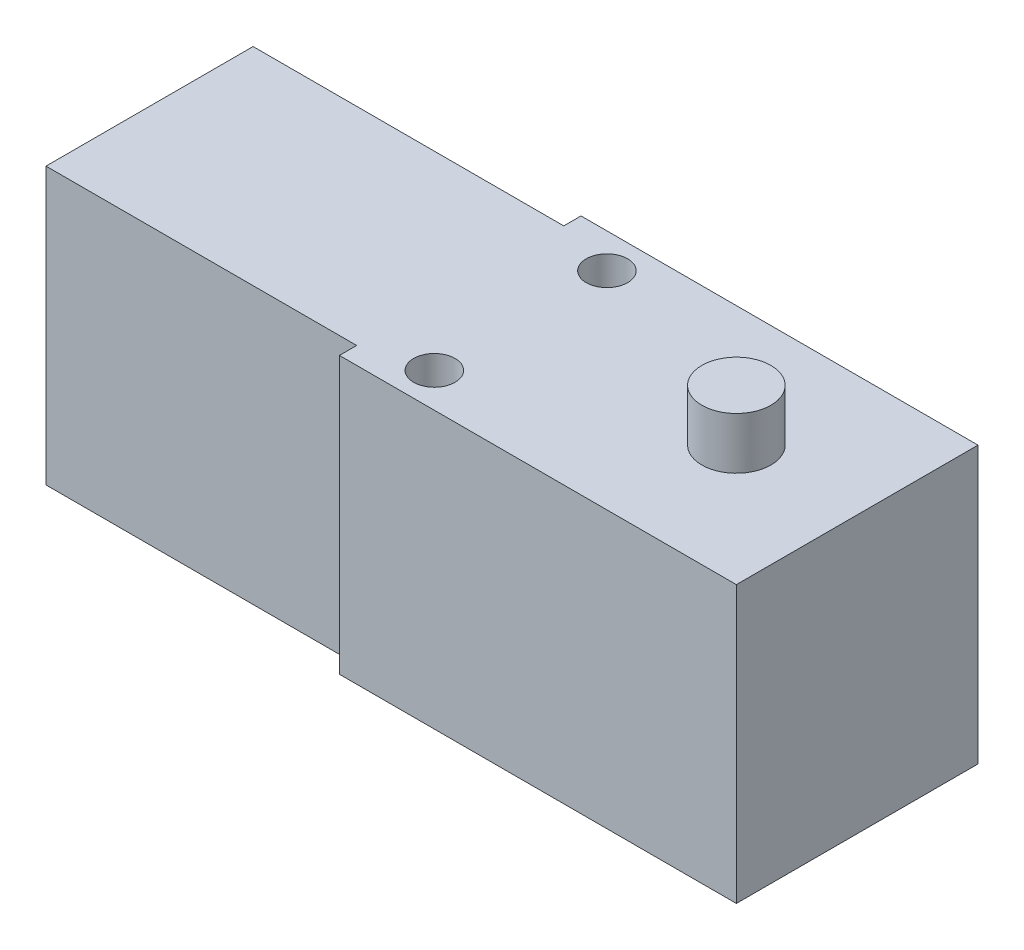
SolidWorks part; units mm, degrees
ref_plane "Front Plane" through (0, 0, 0) normal (0, 0, 1) x (1, 0, 0)
ref_plane "Top Plane" through (0, 0, 0) normal (0, 1, 0) x (1, 0, 0)
ref_plane "Right Plane" through (0, 0, 0) normal (1, 0, 0) x (0, 0, -1)
sketch "Sketch1" plane through (0, 0, 0) normal (0, 1, 0) x (1, 0, 0)
  line L0 (-28.575, 0) -> (36.5125, 0) construction
  line L1 (-28.575, -9.525) -> (0, -9.525)
  line L2 (-28.575, -9.525) -> (-28.575, 9.525)
  line L3 (-28.575, 9.525) -> (0, 9.525)
  line L4 (0, -9.525) -> (0, 9.525)
  line L5 (-28.575, -9.525) -> (0, 9.525) construction
  line L6 (-28.575, 9.525) -> (0, -9.525) construction
  line L7 (36.5125, -11.1125) -> (0, -11.1125)
  line L8 (36.5125, -11.1125) -> (36.5125, 11.1125)
  line L9 (36.5125, 11.1125) -> (0, 11.1125)
  line L10 (0, -11.1125) -> (0, 11.1125)
  line L11 (36.5125, -11.1125) -> (0, 11.1125) construction
  line L12 (36.5125, 11.1125) -> (0, -11.1125) construction
  point P0 (-14.2875, 0)
  point P5 (18.2563, 0)
  point P10 (-8.0454, -12.6923)
  point P13 (-5.5485, -23.3732)
  dimension "D1" = 28.575
  dimension "D2" = 36.5125
  dimension "D3" = 22.225
  dimension "D4" = 19.05
extrude "Boss-Extrude1" add sketch "Sketch1" along normal mid plane 25.4 contours L1 L4 L3 L2 | L10 L7 L8 L9 L4
sketch "Sketch2" plane through (0, 0, 0) normal (0, -1, 0) x (1, 0, 0)
  line L0 (36.5125, 11.1125) -> (36.5125, -11.1125) construction
  circle A0 centre (25.4, 0) radius 3.175
  point P4 (0, 0)
  point P5 (36.5125, 0)
  dimension "D1" = 6.35
  dimension "D2" = 11.1125
extrude "Boss-Extrude2" add sketch "Sketch2" along normal mid plane 34.925
sketch "Sketch3" plane through (0, -12.7, 0) normal (0, -1, 0) x (1, 0, 0)
  line L0 (0, -9.525) -> (0, -11.1125) construction
  line L1 (5.5562, -7.9375) -> (5.5562, 7.9375) construction
  circle A0 centre (5.5562, 7.9375) radius 1.905
  circle A1 centre (5.5562, -7.9375) radius 1.905
  point P4 (0, 0)
  point P7 (25.4, 0)
  point P10 (5.5562, 0)
  dimension "D1" = 3.81
  dimension "D2" = 15.875
  dimension "D3" = 5.5562
extrude "Cut-Extrude1" cut sketch "Sketch3" against normal through all
